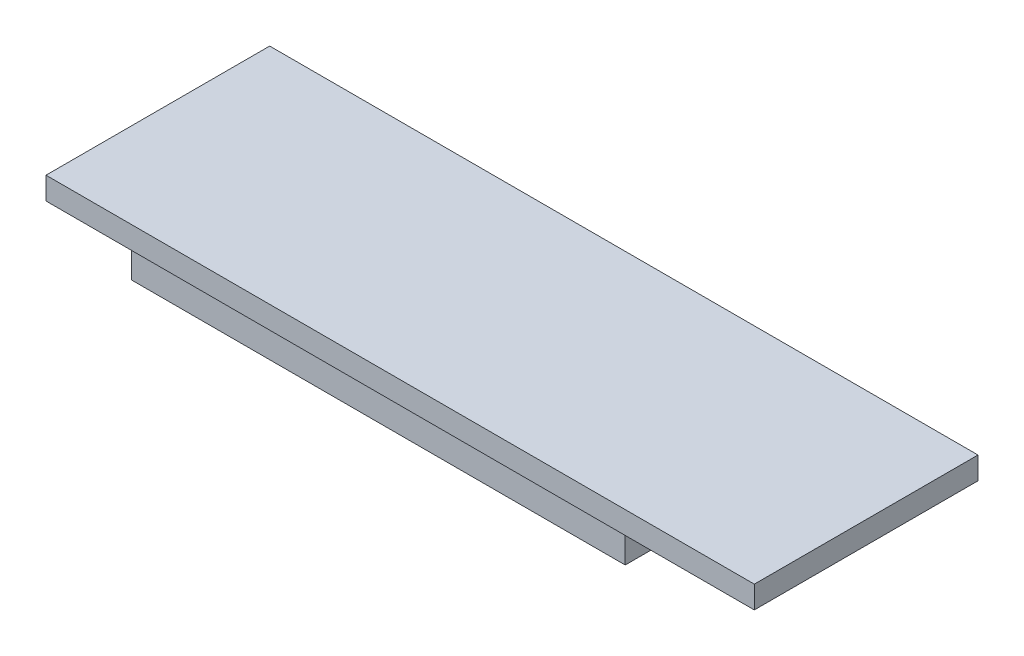
SolidWorks part; units mm, degrees
ref_plane "Front Plane" through (0, 0, 0) normal (0, 0, 1) x (1, 0, 0)
ref_plane "Top Plane" through (0, 0, 0) normal (0, 1, 0) x (1, 0, 0)
ref_plane "Right Plane" through (0, 0, 0) normal (1, 0, 0) x (0, 0, -1)
sketch "Sketch1" plane through (0, 0, 0) normal (0, 1, 0) x (1, 0, 0)
  line L1 (-19, -6) -> (19, -6)
  line L2 (-19, -6) -> (-19, 6)
  line L3 (-19, 6) -> (19, 6)
  line L4 (19, -6) -> (19, 6)
  line L5 (-19, -6) -> (19, 6) construction
  line L6 (-19, 6) -> (19, -6) construction
  point P0 (0, 0)
  dimension "D1" = 12
  dimension "D2" = 38
extrude "Boss-Extrude1" add sketch "Sketch1" along normal mid plane 1.2
sketch "Sketch2" plane through (0, -0.6, 0) normal (0, -1, 0) x (1, 0, 0)
  line L0 (-14.65, 5.775) -> (11.85, 5.775)
  line L1 (-14.65, 5.775) -> (-14.65, -5.775)
  line L2 (-14.65, -5.775) -> (11.85, -5.775)
  line L3 (11.85, 5.775) -> (11.85, -5.775)
  line L4 (-19, -6) -> (-19, 6) construction
  line L5 (-19, 6) -> (19, 6) construction
  dimension "D1" = 4.35
  dimension "D2" = 11.55
  dimension "D3" = 26.5
  dimension "D4" = 0.225
extrude "Boss-Extrude2" add sketch "Sketch2" along normal blind 1.6 contours L1 L2 L3 L0
